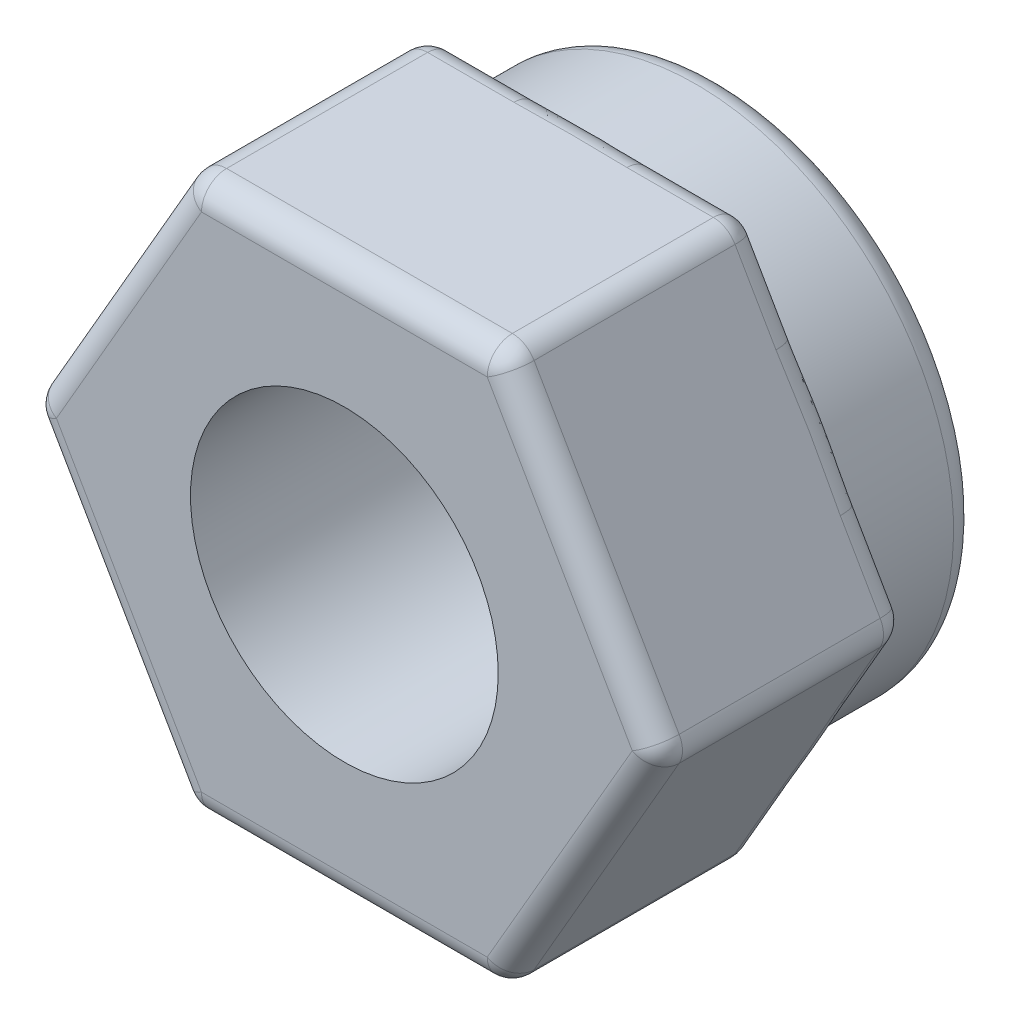
SolidWorks part; units mm, degrees
ref_plane "Front Plane" through (0, 0, 0) normal (0, 0, 1) x (1, 0, 0)
ref_plane "Top Plane" through (0, 0, 0) normal (0, 1, 0) x (1, 0, 0)
ref_plane "Right Plane" through (0, 0, 0) normal (1, 0, 0) x (0, 0, -1)
sketch "Sketch1" plane through (0, 0, 0) normal (0, 0, 1) x (1, 0, 0)
  line L0 (3.1822, 5.588) -> (-3.1822, 5.588)
  line L1 (-3.1822, 5.588) -> (-6.4085, 0)
  line L2 (-6.4085, 0) -> (-3.1822, -5.588)
  line L3 (-3.1822, -5.588) -> (3.1822, -5.588)
  line L4 (3.1822, -5.588) -> (6.4085, 0)
  line L5 (6.4085, 0) -> (3.1822, 5.588)
  line L6 (0, 0) -> (0, 5.588) construction
  line L7 (0, 0) -> (6.4085, 0) construction
  circle A0 centre (0, 0) radius 3.1115
  dimension "D2" = 6.223
  dimension "D1" = 11.176
  dimension "D3" = 6.3645
  dimension "D4" = 12.8169
extrude "Extrude1" add sketch "Sketch1" against normal blind 5.08
sketch "Sketch2" plane through (0, 0, -5.08) normal (0, 0, -1) x (-1, 0, 0)
  circle A0 centre (0, 0) radius 5.207
  circle A1 centre (0, 0) radius 3.1115 construction
  circle A2 centre (0, 0) radius 3.1115
  dimension "D1" = 10.414
extrude "Extrude2" add sketch "Sketch2" along normal blind 2.54
fillet "Fillet1" radius 0.508 19 edges at (-5.207, 0, -7.62) (-4.7954, 2.794, -5.08) (0, 5.588, -5.08) (4.7954, 2.794, -5.08) (4.7954, -2.794, -5.08) (0, -5.588, -5.08) (-4.7954, -2.794, -5.08) (3.1822, -5.588, -2.54) (6.4085, 0, -2.54) (3.1822, 5.588, -2.54) (-3.1822, 5.588, -2.54) (0, 5.588, 0) (4.7954, 2.794, 0) (4.7954, -2.794, 0) (0, -5.588, 0) (-3.1822, -5.588, -2.54) (-4.7954, -2.794, 0) (-4.7954, 2.794, 0) (-6.4085, 0, -2.54)
